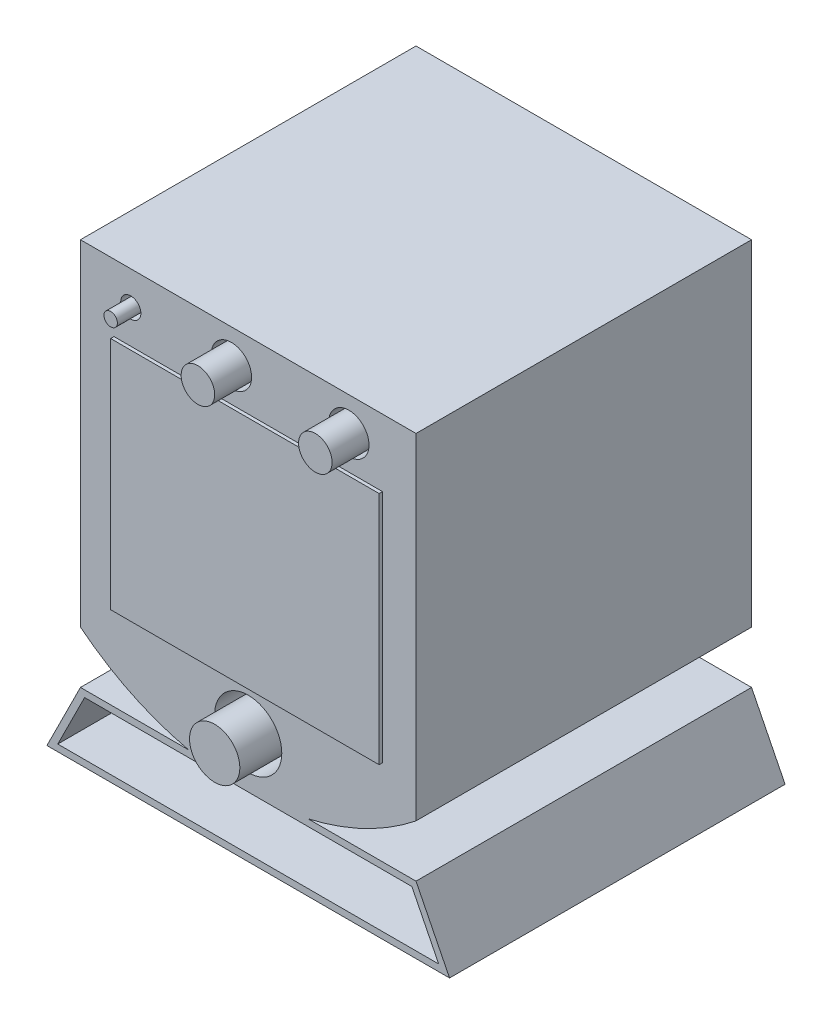
SolidWorks part; units mm, degrees
ref_plane "前视基准面" through (0, 0, 0) normal (0, 0, 1) x (1, 0, 0)
ref_plane "上视基准面" through (0, 0, 0) normal (0, 1, 0) x (1, 0, 0)
ref_plane "右视基准面" through (0, 0, 0) normal (1, 0, 0) x (0, 0, -1)
sketch "草图1" plane through (0, 0, 0) normal (0, 0, 1) x (1, 0, 0)
  line L0 (0, 57.9807) -> (0, -59.9214) construction
  line L1 (-50, 10.7965) -> (50, 10.7965)
  line L2 (50, 10.7965) -> (60, -9.2035)
  line L3 (60, -9.2035) -> (-60, -9.2035)
  line L4 (-50, 10.7965) -> (-60, -9.2035)
  point P8 (0, -9.2035)
  point P9 (0, 10.7965)
  dimension "D1" = 50
  dimension "D2" = 60
  dimension "D3" = 20
extrude "拉伸-薄壁1" add sketch "草图1" along normal mid plane 100 thin
sketch "草图2" plane through (0, 0, 0) normal (0, 0, 1) x (1, 0, 0)
  line L1 (50, 26.3465) -> (50, 126.3465)
  line L2 (0, 40.6016) -> (0, 20.1855) construction
  line L3 (-50, 26.3465) -> (-50, 126.3465)
  line L4 (-50, 126.3465) -> (50, 126.3465)
  arc A0 (-50, 26.3465) -> (50, 26.3465) centre (0, 88.7965) ccw
  dimension "D1" = 80
  dimension "D3" = 100
extrude "凸台-拉伸1" add sketch "草图2" along normal mid plane 100
sketch "草图3" plane through (0, 0, 50) normal (0, 0, 1) x (1, 0, 0)
  line L0 (50, 26.3465) -> (50, 126.3465) construction
  line L1 (-40, 106.3465) -> (40, 106.3465)
  line L2 (-40, 106.3465) -> (-40, 36.3465)
  line L3 (-40, 36.3465) -> (40, 36.3465)
  line L4 (40, 106.3465) -> (40, 36.3465)
  line L5 (50, 126.3465) -> (-50, 126.3465) construction
  dimension "D1" = 10
  dimension "D2" = 20
  dimension "D3" = 70
  dimension "D4" = 80
extrude "凸台-拉伸2" add sketch "草图3" along normal blind 1
sketch "草图4" plane through (0, 0, 50) normal (0, 0, 1) x (1, 0, 0)
  line L0 (50, 26.3465) -> (50, 126.3465) construction
  line L1 (48.7639, 8.7965) -> (-48.7639, 8.7965) construction
  line L2 (50, 126.3465) -> (-50, 126.3465) construction
  line L3 (-50, 126.3465) -> (-50, 26.3465) construction
  circle A0 centre (-35, 116.3465) radius 3
  circle A1 centre (-5, 116.3465) radius 6
  circle A2 centre (30, 116.3465) radius 6
  circle A3 centre (0, 23.7965) radius 10
  point P12 (1.909, 17.3963)
  point P13 (4.3738, 18.0438)
  point P18 (0, 0)
  point P19 (0, 0)
  dimension "D1" = 20
  dimension "D4" = 6
  dimension "D5" = 12
  dimension "D6" = 12
  dimension "D2" = 50
  dimension "D3" = 15
  dimension "D7" = 10
  dimension "D8" = 15
  dimension "D9" = 30
  dimension "D10" = 35
extrude "切除-拉伸1" cut sketch "草图4" against normal blind 10
sketch "草图5" plane through (0, 0, 40) normal (0, 0, 1) x (1, 0, 0)
  circle A0 centre (0, 23.7965) radius 7.5
  circle A1 centre (-5, 116.3465) radius 5
  circle A2 centre (30, 116.3465) radius 5
  dimension "D1" = 10
  dimension "D2" = 10
  dimension "D3" = 15
extrude "凸台-拉伸3" add sketch "草图5" along normal blind 20
sketch "草图6" plane through (0, 0, 40) normal (0, 0, 1) x (1, 0, 0)
  circle A0 centre (-35, 116.3465) radius 2
  dimension "D1" = 4
extrude "凸台-拉伸4" add sketch "草图6" along normal blind 16
